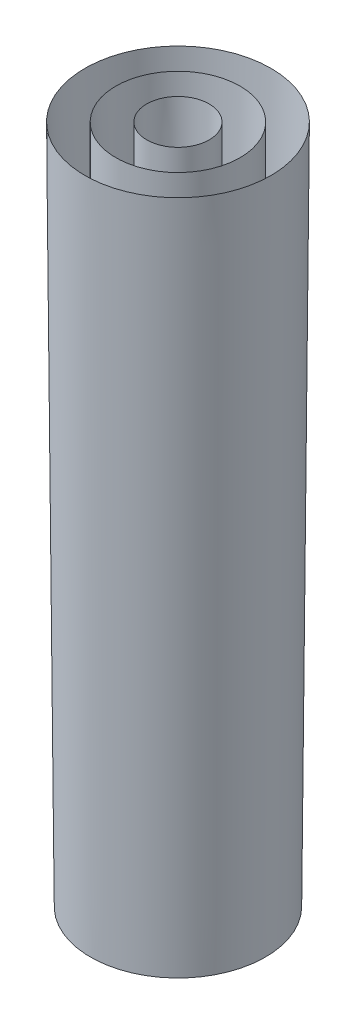
SolidWorks part; units mm, degrees
ref_plane "Спереди" through (0, 0, 0) normal (0, 0, 1) x (1, 0, 0)
ref_plane "Сверху" through (0, 0, 0) normal (0, 1, 0) x (1, 0, 0)
ref_plane "Справа" through (0, 0, 0) normal (1, 0, 0) x (0, 0, -1)
sketch "Эскиз1" plane through (0, 0, 0) normal (0, 0, 1) x (1, 0, 0)
  line L0 (29.7378, 0) -> (-2.6241, 0) construction
  line L1 (-2.6204, 145) -> (32.8417, 145) construction
  line L2 (-2.6877, -0.114) -> (-2.6877, 1.4253) construction
  line L4 (15.9795, 0) -> (16.3759, 0) construction
  line L7 (-2.6241, 0) -> (3.9657, 145)
  line L8 (3.9657, 145) -> (3.9657, 0)
  line L9 (3.9657, 0) -> (10.5556, 145)
  line L10 (10.5556, 145) -> (10.5556, 0)
  line L11 (10.5556, 0) -> (17.1454, 145)
  line L12 (17.1454, 145) -> (15.9795, 0)
  line L14 (-1.9357, 0) -> (3.2203, 109.9488)
  line L15 (3.2203, 109.9488) -> (3.5248, -0.3791)
  line L16 (3.5248, -0.3791) -> (4.2941, -0.3791)
  line L17 (4.2941, -0.3791) -> (4.6001, 6.148)
  line L18 (4.6001, 6.148) -> (9.4678, 109.9488)
  line L19 (9.4678, 109.9488) -> (10.1869, -0.4252)
  line L20 (10.1869, -0.4252) -> (11.0095, -0.4252)
  line L21 (11.0095, -0.4252) -> (11.6843, 13.9634)
  line L22 (11.6843, 13.9634) -> (15.8523, 110.4725)
  line L23 (15.8523, 110.4725) -> (15.3118, 0)
  line L25 (15.3118, 0) -> (15.9795, 0)
  line L26 (-2.6241, 0) -> (-1.9357, 0)
  line L27 (-2.6241, 0) -> (-2.6241, 1.141) construction
  point P22 (3.9657, 0)
  dimension "D1" = 145
  dimension "D2" = 19
revolve "Повернуть1" add sketch "Эскиз1" angle 360 about L2
